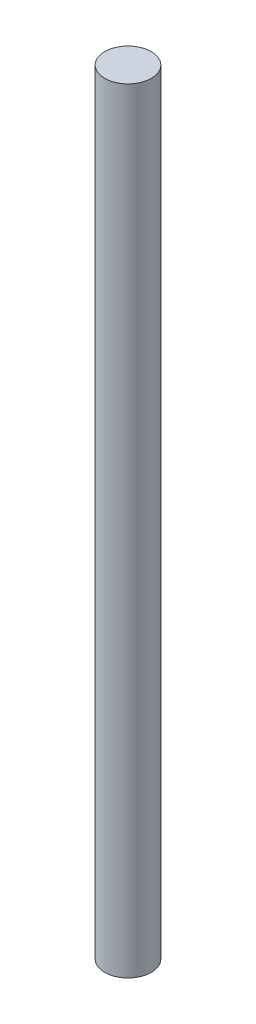
SolidWorks part; units mm, degrees
ref_plane "Front Plane" through (0, 0, 0) normal (0, 0, 1) x (1, 0, 0)
ref_plane "Top Plane" through (0, 0, 0) normal (0, 1, 0) x (1, 0, 0)
ref_plane "Right Plane" through (0, 0, 0) normal (1, 0, 0) x (0, 0, -1)
sketch "Sketch1" plane through (0, 0, 0) normal (0, 1, 0) x (1, 0, 0)
  circle A0 centre (0, 0) radius 6
  dimension "D1" = 12
extrude "Boss-Extrude1" add sketch "Sketch1" along normal blind 200
